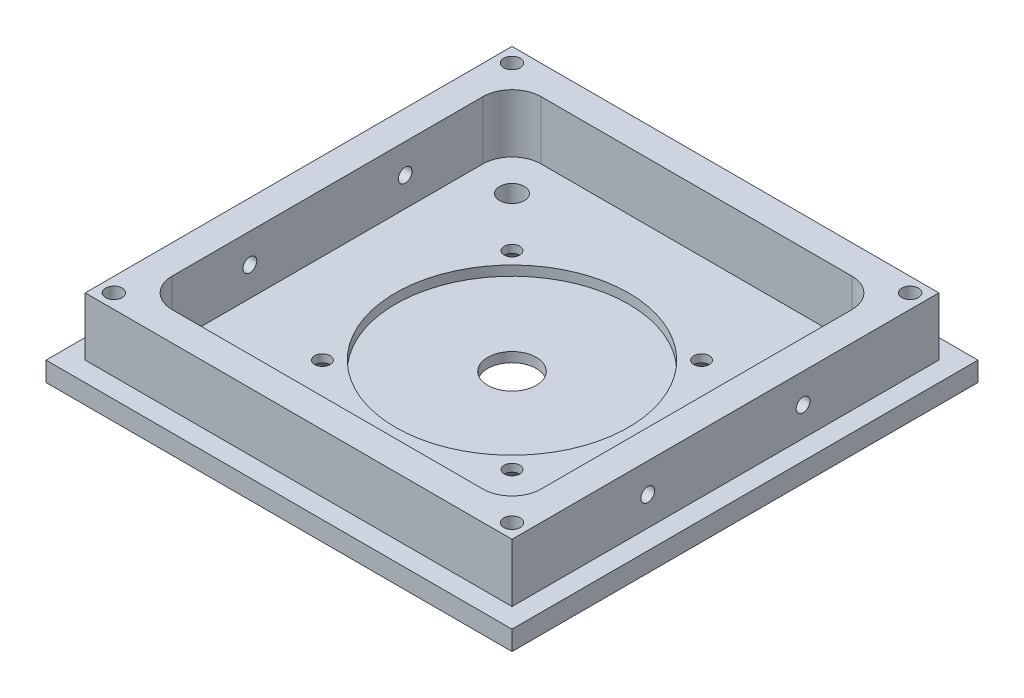
SolidWorks part; units mm, degrees
material "6061-T6 (SS)"
ref_plane "Front Plane" through (0, 0, 0) normal (0, 0, 1) x (1, 0, 0)
ref_plane "Top Plane" through (0, 0, 0) normal (0, 1, 0) x (1, 0, 0)
ref_plane "Right Plane" through (0, 0, 0) normal (1, 0, 0) x (0, 0, -1)
sketch "Sketch1" plane through (0, 0, 0) normal (0, 1, 0) x (1, 0, 0)
  line L1 (-38.1, -38.1) -> (38.1, -38.1)
  line L2 (-38.1, -38.1) -> (-38.1, 38.1)
  line L3 (-38.1, 38.1) -> (38.1, 38.1)
  line L4 (38.1, -38.1) -> (38.1, 38.1)
  line L5 (-38.1, -38.1) -> (38.1, 38.1) construction
  line L6 (-38.1, 38.1) -> (38.1, -38.1) construction
  point P0 (0, 0)
  dimension "D1" = 76.2
  dimension "D2" = 76.2
extrude "Boss-Extrude1" add sketch "Sketch1" along normal blind 3.175
sketch "Sketch2" plane through (0, 3.175, 0) normal (0, 1, 0) x (1, 0, 0)
  line L0 (-38.1, 38.1) -> (-38.1, -38.1) construction
  line L1 (34.8971, -34.8971) -> (-34.8971, -34.8971)
  line L2 (34.8971, -34.8971) -> (34.8971, 34.8971)
  line L3 (34.8971, 34.8971) -> (-34.8971, 34.8971)
  line L4 (-34.8971, -34.8971) -> (-34.8971, 34.8971)
  line L5 (34.8971, -34.8971) -> (-34.8971, 34.8971) construction
  line L6 (34.8971, 34.8971) -> (-34.8971, -34.8971) construction
  line L7 (30.1625, -30.1625) -> (-30.1625, -30.1625)
  line L8 (30.1625, -30.1625) -> (30.1625, 30.1625)
  line L9 (30.1625, 30.1625) -> (-30.1625, 30.1625)
  line L10 (-30.1625, -30.1625) -> (-30.1625, 30.1625)
  line L11 (30.1625, -30.1625) -> (-30.1625, 30.1625) construction
  line L12 (30.1625, 30.1625) -> (-30.1625, -30.1625) construction
  line L14 (38.1, 38.1) -> (-38.1, 38.1) construction
  point P0 (0, 0)
  point P6 (0, 0)
  dimension "D1" = 3.2029
  dimension "D2" = 3.2029
  dimension "D3" = 60.325
extrude "Boss-Extrude2" add sketch "Sketch2" along normal blind 9.525 contours L10 L9 L8 L7
fillet "Fillet1" radius 4.7625 4 edges at (-30.1625, 7.9375, 30.1625) (30.1625, 7.9375, 30.1625) (30.1625, 7.9375, -30.1625) (-30.1625, 7.9375, -30.1625)
sketch "Sketch3" plane through (0, 3.175, 0) normal (0, 1, 0) x (1, 0, 0)
  circle A0 centre (0, 0) radius 19.05
  dimension "D1" = 38.1
extrude "Cut-Extrude1" cut sketch "Sketch3" against normal blind 1.5875
sketch "Sketch4" plane through (0, 1.5875, 0) normal (0, 1, 0) x (1, 0, 0)
  circle A0 centre (0, 0) radius 3.9688
  dimension "D1" = 7.9375
extrude "Cut-Extrude2" cut sketch "Sketch4" against normal through all
sketch "Sketch5" plane through (0, 3.175, 0) normal (0, 1, 0) x (1, 0, 0)
  line L1 (15.5, -15.5) -> (-15.5, -15.5)
  line L2 (15.5, -15.5) -> (15.5, 15.5)
  line L3 (15.5, 15.5) -> (-15.5, 15.5)
  line L4 (-15.5, -15.5) -> (-15.5, 15.5)
  line L5 (15.5, -15.5) -> (-15.5, 15.5) construction
  line L6 (15.5, 15.5) -> (-15.5, -15.5) construction
  line L7 (23.5966, -23.5966) -> (-23.5966, -23.5966)
  line L8 (23.5966, -23.5966) -> (23.5966, 23.5966)
  line L9 (23.5966, 23.5966) -> (-23.5966, 23.5966)
  line L10 (-23.5966, -23.5966) -> (-23.5966, 23.5966)
  line L11 (23.5966, -23.5966) -> (-23.5966, 23.5966) construction
  line L12 (23.5966, 23.5966) -> (-23.5966, -23.5966) construction
  circle A0 centre (-15.5, 15.5) radius 1.2637
  circle A1 centre (15.5, 15.5) radius 1.2637
  circle A2 centre (15.5, -15.5) radius 1.2637
  circle A3 centre (-15.5, -15.5) radius 1.2637
  point P2 (0, 0)
  point P10 (0, 0)
  dimension "D2" = 2.5273
  dimension "D1" = 31
  dimension "D3" = 47.1932
hole_wizard "#39 (0.0995) Diameter Hole1" positions "Sketch7" profile "Sketch6" hole size "#39" standard "ANSI Inch" end condition through all
sketch "Sketch7" plane through (0, 3.175, 0) normal (0, 1, 0) x (1, 0, 0)
  point P0 (15.5, 15.5)
  point P3 (-15.5, 15.5)
  point P6 (-15.5, -15.5)
  point P9 (15.5, -15.5)
  point P12 (-23.5966, 23.5966)
  point P15 (23.5966, 23.5966)
  point P18 (23.5966, -23.5966)
  point P21 (-23.5966, -23.5966)
sketch "Sketch6" plane through (15.5, 3.175, -15.5) normal (1, 0, 0) x (0, 0, 1)
  line L0 (0, 0) -> (0, 3.175)
  line L1 (0, 3.175) -> (1.2636, 3.175)
  line L2 (1.2636, 3.175) -> (1.2636, 0)
  line L5 (1.2636, 0) -> (0, 0)
  line L11 (0, -6.35) -> (0, 107.95) construction
  dimension "Thru Hole Dia." = 2.5273
  dimension "Thru Hole Depth" = 3.175
hole_wizard "#10-32 Tapped Hole1" positions "Sketch17" profile "Sketch15" tap size "#10-32" standard "ANSI Inch" end condition through all
sketch "Sketch17" plane through (0, 3.175, 0) normal (0, 1, 0) x (1, 0, 0)
  point P0 (-23.5966, 23.5966)
  point P3 (23.5966, 23.5966)
  point P6 (23.5966, -23.5966)
  point P9 (-23.5966, -23.5966)
sketch "Sketch15" plane through (-23.5966, 3.175, -23.5966) normal (1, 0, 0) x (0, 0, 1)
  line L0 (0, 0) -> (0, 3.175)
  line L1 (0, 3.175) -> (2.0193, 3.175)
  line L2 (2.0193, 3.175) -> (2.0193, 0)
  line L5 (2.0193, 0) -> (0, 0)
  line L11 (0, -6.35) -> (0, 107.95) construction
  dimension "Thru Tap Drill Dia." = 4.0386
  dimension "Thru Tap Drill Depth" = 3.175
cosmetic thread "Hole Thread3" parameters "D2"=4.826
cosmetic thread "Hole Thread4" parameters "D2"=4.826
cosmetic thread "Hole Thread5" parameters "D2"=4.826
cosmetic thread "Hole Thread6" parameters "D2"=4.826
sketch "Sketch8" plane through (34.8971, 0, 0) normal (1, 0, 0) x (0, 0, -1)
  line L0 (-38.1, 3.175) -> (38.1, 3.175) construction
  point P0 (-12.7, 7.9375)
  dimension "D1" = 4.7625
  dimension "D2" = 12.7
hole_wizard "#4-40 Tapped Hole1" positions "Sketch10" profile "Sketch9" tap size "#4-40" standard "ANSI Inch"
sketch "Sketch10" plane through (34.8971, 0, 0) normal (1, 0, 0) x (0, 0, -1)
  point P0 (-12.7, 7.9375)
sketch "Sketch9" plane through (34.8971, 7.9375, 12.7) normal (0, 1, 0) x (0, 0, -1)
  line L0 (0, 0) -> (0, 7.2832)
  line L1 (0, 7.2832) -> (1.1303, 6.604)
  line L2 (1.1303, 6.604) -> (1.1303, 0)
  line L5 (1.1303, 0) -> (0, 0)
  line L10 (0, 7.2832) -> (-1.1303, 6.604) construction
  line L11 (0, -6.35) -> (0, 107.95) construction
  dimension "Tap Drill Dia." = 2.2606
  dimension "Tap Drill Depth" = 6.604
  dimension "Drill Angle" = 118
cosmetic thread "Hole Thread1" parameters "D1"=2.4486, "D2"=2.8448
mirror "Mirror1" about plane through (0, 0, 0) normal (0, 0, 1) of "#4-40 Tapped Hole1"
mirror "Mirror2" about plane through (0, 0, 0) normal (1, 0, 0) of "Mirror1", "#4-40 Tapped Hole1"
chamfer "Chamfer1" distance 1.905 angle 41 4 edges at (-15.5, 0, -14.2363) (15.5, 0, -14.2364) (15.5, 0, 16.7636) (-15.5, 0, 16.7637)
sketch "Sketch11" plane through (0, 0, 0) normal (0, -1, 0) x (1, 0, 0)
  circle A0 centre (32.5501, -32.5501) radius 2.032
  dimension "D1" = 4.064
hole_wizard "#6-32 Tapped Hole1" positions "Sketch13" profile "Sketch12" tap size "#6-32" standard "ANSI Inch" end condition through all
sketch "Sketch13" plane through (0, 0, 0) normal (0, -1, 0) x (-1, 0, 0)
  point P0 (-32.5501, 32.5501)
sketch "Sketch12" plane through (32.5501, 0, -32.5501) normal (1, 0, 0) x (0, 0, -1)
  line L0 (0, 0) -> (0, 12.7)
  line L1 (0, 12.7) -> (1.3525, 12.7)
  line L2 (1.3525, 12.7) -> (1.3525, 0)
  line L5 (1.3525, 0) -> (0, 0)
  line L11 (0, -6.35) -> (0, 107.95) construction
  dimension "Thru Tap Drill Dia." = 2.7051
  dimension "Thru Tap Drill Depth" = 12.7
cosmetic thread "Hole Thread2" parameters "D2"=3.5052
pattern_circular "CirPattern1" count 4 over 360 about axis through (0, 0, 0) along (0, 1, 0) of "#6-32 Tapped Hole1"
equation "\"D2@Sketch2\"=\"D1@Sketch2\""
equation "\"D2@Sketch1\"=\"D1@Sketch1\""
